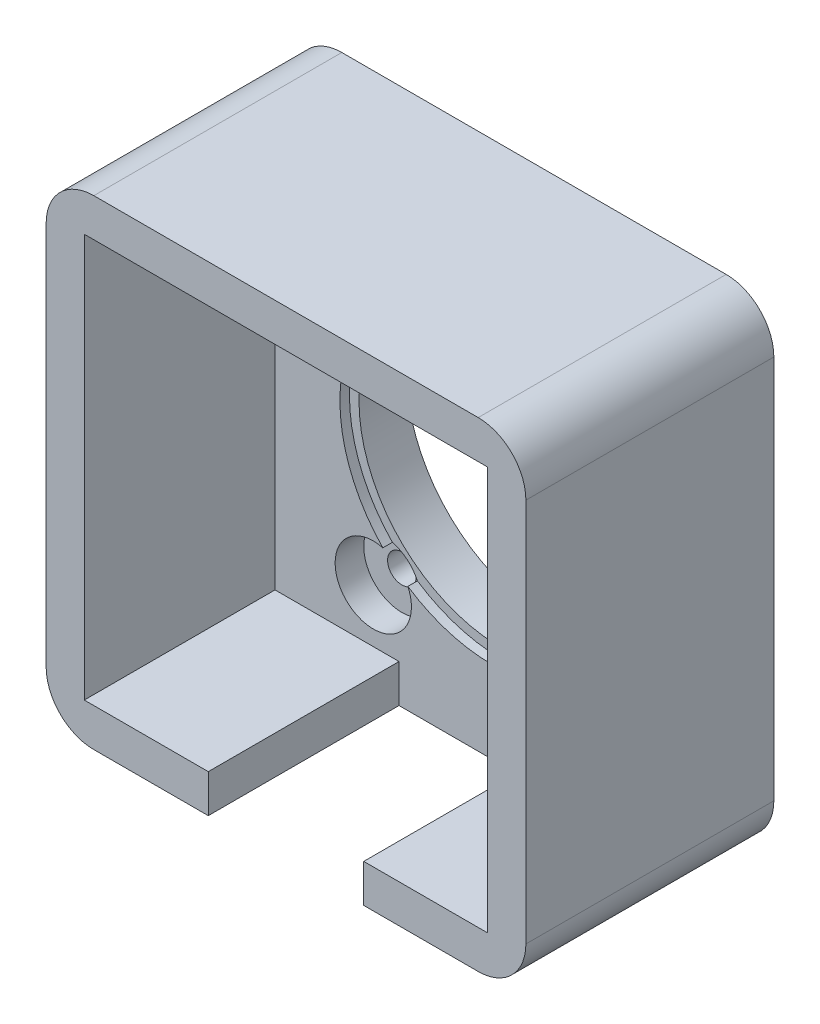
SolidWorks part; units mm, degrees
ref_plane "Front" through (0, 0, 0) normal (0, 0, 1) x (1, 0, 0)
ref_plane "Top" through (0, 0, 0) normal (0, 1, 0) x (1, 0, 0)
ref_plane "Right" through (0, 0, 0) normal (1, 0, 0) x (0, 0, -1)
sketch "Esquisse1" plane through (0, 0, 0) normal (0, 0, 1) x (1, 0, 0)
  line L1 (0, 0) -> (50.3, 0)
  line L2 (0, 0) -> (0, 50.3)
  line L3 (0, 50.3) -> (50.3, 50.3)
  line L4 (50.3, 0) -> (50.3, 50.3)
  dimension "D1" = 50.3
  dimension "D2" = 50.3
extrude "Boss.-Extru.1" add sketch "Esquisse1" along normal blind 6
sketch "Esquisse2" plane through (0, 0, 6) normal (0, 0, 1) x (1, 0, 0)
  line L0 (50.3, 50.3) -> (0, 50.3) construction
  line L1 (4, 46.3) -> (46.3, 46.3)
  line L2 (4, 46.3) -> (4, 4)
  line L3 (4, 4) -> (17, 4)
  line L4 (46.3, 46.3) -> (46.3, 4)
  line L5 (0, 0) -> (50.3, 0) construction
  line L6 (0, 50.3) -> (0, 0) construction
  line L7 (50.3, 0) -> (50.3, 50.3) construction
  line L8 (33.3, 4) -> (46.3, 4)
  line L9 (33.3, 0) -> (50.3, 0)
  line L10 (17, 4) -> (17, 0)
  line L11 (0, 50.3) -> (50.3, 50.3)
  line L12 (33.3, 4) -> (33.3, 0)
  line L13 (0, 50.3) -> (0, 0)
  line L14 (0, 0) -> (17, 0)
  line L15 (50.3, 50.3) -> (50.3, 0)
  point P16 (17, 2)
  point P17 (33.3, 2)
  dimension "D1" = 4
  dimension "D2" = 4
  dimension "D3" = 4
  dimension "D4" = 4
  dimension "D5" = 16.3
  dimension "D6" = 13
extrude "Boss.-Extru.2" add sketch "Esquisse2" along normal blind 20
sketch "Esquisse3" plane through (0, 0, 0) normal (0, 0, -1) x (-1, 0, 0)
  line L4 (-50.3, 50.3) -> (0, 50.3) construction
  line L6 (0, 0) -> (-50.3, 0) construction
  line L7 (-50.3, 0) -> (-50.3, 50.3) construction
  circle A0 centre (-39.3, 39.6) radius 1.5
  circle A1 centre (-14.3, 39.6) radius 1.5
  circle A2 centre (-14.3, 9.6) radius 1.5
  circle A4 centre (-39.3, 9.6) radius 1.5
  dimension "D2" = 3
  dimension "D3" = 3
  dimension "D4" = 3
  dimension "D5" = 3
  dimension "D12" = 11
  dimension "D6" = 25
  dimension "D7" = 10.7
  dimension "D8" = 30
  dimension "D9" = 9.6
  dimension "D10" = 10.7
  dimension "D11" = 11
  dimension "D13" = 25
extrude "Enlèv. mat.-Extru.1" cut sketch "Esquisse3" against normal through all
fillet "Congé2" radius 5 1 edges at (0, 50.3, 13)
sketch "Esquisse4" plane through (0, 0, 6) normal (0, 0, 1) x (1, 0, 0)
  circle A0 centre (14.3, 39.6) radius 4
  circle A1 centre (39.3, 39.6) radius 4
  circle A2 centre (39.3, 9.6) radius 4
  circle A3 centre (14.3, 9.6) radius 4
  dimension "D1" = 8
  dimension "D2" = 8
  dimension "D3" = 8
  dimension "D4" = 8
extrude "Enlèv. mat.-Extru.2" cut sketch "Esquisse4" against normal blind 3
fillet "Congé6" radius 5 3 edges at (50.3, 50.3, 13) (0, 0, 13) (50.3, 0, 13)
sketch "Esquisse5" plane through (0, 0, 6) normal (0, 0, 1) x (1, 0, 0)
  line L0 (39.3, 39.6) -> (14.3, 9.6)
  circle A0 centre (26.8, 24.6) radius 16
  dimension "D1" = 32
extrude "Enlèv. mat.-Extru.3" cut sketch "Esquisse5" against normal blind 1 contours A0
sketch "Esquisse6" plane through (0, 0, 5) normal (0, 0, 1) x (1, 0, 0)
  circle A0 centre (26.8, 24.6) radius 15
  arc A1 (15.3035, 35.7279) -> (15.3035, 13.4721) centre (26.8, 24.6) ccw construction
  dimension "D1" = 30
extrude "Enlèv. mat.-Extru.4" cut sketch "Esquisse6" against normal blind 21
